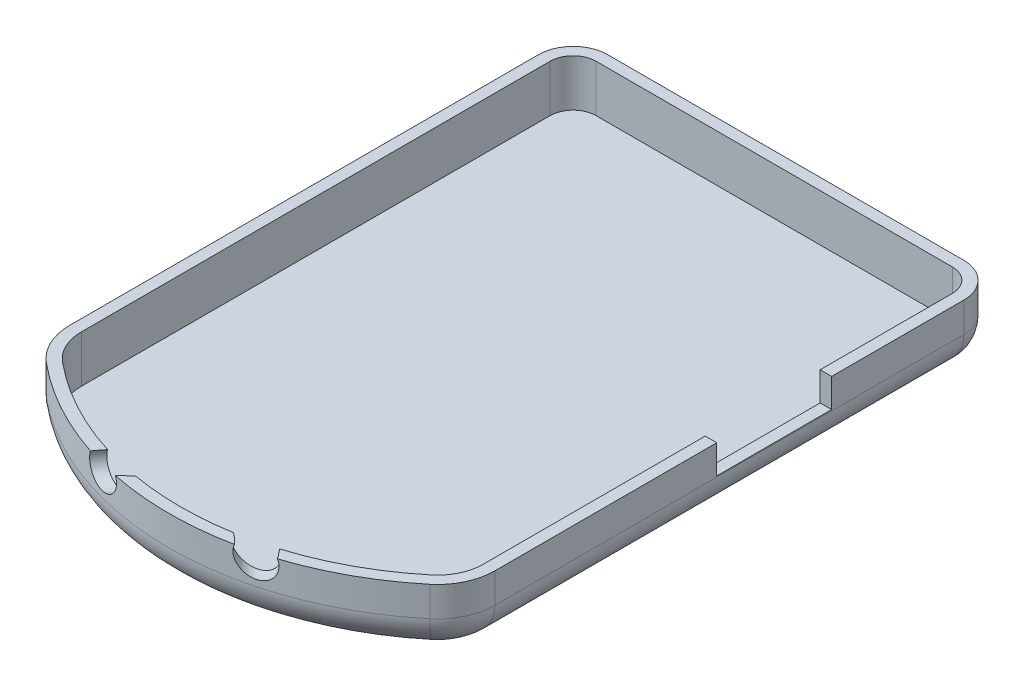
SolidWorks part; units mm, degrees
ref_plane "Front Plane" through (0, 0, 0) normal (0, 0, 1) x (1, 0, 0)
ref_plane "Top Plane" through (0, 0, 0) normal (0, 1, 0) x (1, 0, 0)
ref_plane "Right Plane" through (0, 0, 0) normal (1, 0, 0) x (0, 0, -1)
sketch "Sketch1" plane through (0, 0, 0) normal (0, 1, 0) x (1, 0, 0)
  line L0 (0, -43.7979) -> (0, -43)
  line L1 (3, 0) -> (34, 0)
  line L2 (0, -3) -> (0, -43)
  line L4 (37, -3) -> (37, -43)
  line L7 (37, -43) -> (37, -43.7979)
  arc A2 (34, 0) -> (37, -3) centre (34, -3) cw
  arc A3 (0, -3) -> (3, 0) centre (3, -3) cw
  arc A4 (35.1895, -47.6484) -> (1.8105, -47.6484) centre (18.5, -27.5) cw
  arc A5 (35.1895, -47.6484) -> (37, -43.7979) centre (32, -43.7979) ccw
  arc A6 (1.8105, -47.6484) -> (0, -43.7979) centre (5, -43.7979) cw
  point P9 (37, -46)
  point P12 (37, 0)
  point P15 (0, 0)
  dimension "D3" = 5
  dimension "D1" = 37
  dimension "D2" = 46
  dimension "D4" = 40
extrude "Boss-Extrude1" add sketch "Sketch1" along normal blind 1.5
ref_plane "Plane1" through (0, 1.5, 0) normal (0, 1, 0) x (1, 0, 0)
sketch "Sketch2" plane through (0, 1.5, 0) normal (0, 1, 0) x (1, 0, 0)
  line L0 (0, -43.7979) -> (0, -43)
  line L1 (3, 0) -> (34, 0)
  line L2 (0, -3) -> (0, -43)
  line L4 (37, -3) -> (37, -43)
  line L9 (37, -43) -> (37, -43.7979)
  line L10 (1, -43.7979) -> (1, -43)
  line L11 (1, -3) -> (1, -43)
  line L14 (3, -1) -> (34, -1)
  line L15 (36, -3) -> (36, -43)
  line L16 (36, -43) -> (36, -43.7979)
  arc A0 (34, 0) -> (37, -3) centre (34, -3) cw
  arc A3 (3, 0) -> (0, -3) centre (3, -3) ccw
  arc A8 (35.1895, -47.6484) -> (1.8105, -47.6484) centre (18.5, -27.5) cw
  arc A9 (1.8105, -47.6484) -> (0, -43.7979) centre (5, -43.7979) cw
  arc A10 (35.1895, -47.6484) -> (37, -43.7979) centre (32, -43.7979) ccw
  arc A14 (2.4484, -46.8783) -> (1, -43.7979) centre (5, -43.7979) cw
  arc A17 (3, -1) -> (1, -3) centre (3, -3) ccw
  arc A18 (34, -1) -> (36, -3) centre (34, -3) cw
  arc A19 (34.5516, -46.8783) -> (36, -43.7979) centre (32, -43.7979) ccw
  arc A20 (34.5516, -46.8783) -> (2.4484, -46.8783) centre (18.5, -27.5) cw
  point P7 (37, 0)
  point P12 (37, -46)
  point P15 (0, 0)
  point P22 (36, -1)
  point P25 (36, -45)
  point P30 (1, -1)
  point P38 (37, -46)
  point P40 (35.5, -43.7979)
  point P41 (32, -43.7979)
  point P42 (34.2327, -46.4933)
  point P44 (2.7673, -46.4933)
  point P45 (5, -43.7979)
  point P46 (1.5, -43.7979)
  dimension "D3" = 3
  dimension "D9" = 5
  dimension "D1" = 37
  dimension "D2" = 46
  dimension "D4" = 35
  dimension "D5" = 44
  dimension "D7" = 1
extrude "Boss-Extrude2" add sketch "Sketch2" along normal blind 1.6
ref_plane "Plane2" through (0, 3.1, 0) normal (0, 1, 0) x (1, 0, 0)
sketch "Sketch3" plane through (0, 3.1, 0) normal (0, 1, 0) x (1, 0, 0)
  line L0 (0, -43.7979) -> (0, -43)
  line L1 (3, 0) -> (34, 0)
  line L2 (0, -3) -> (0, -43)
  line L4 (37, -3) -> (37, -14.5)
  line L9 (37, -43) -> (37, -43.7979)
  line L15 (36, -14.5) -> (37, -14.5)
  line L16 (36, -24.5) -> (37, -24.5)
  line L17 (37, -24.5) -> (37, -43)
  line L19 (36, -25.5) -> (36, -43)
  line L20 (36, -43) -> (36, -43.7979)
  line L21 (1, -43.7979) -> (1, -43)
  line L22 (1, -3) -> (1, -43)
  line L23 (3, -1) -> (34, -1)
  line L24 (36, -3) -> (36, -13.5)
  line L25 (36, -25.5) -> (36, -24.5)
  line L26 (36, -13.5) -> (36, -14.5)
  line L28 (35.5, -14.5) -> (37, -14.5) construction
  line L29 (35.5, -13.5) -> (36, -13.5) construction
  line L32 (35.5, -24.5) -> (37, -24.5) construction
  line L33 (35.5, -25.5) -> (36, -25.5) construction
  arc A0 (34, 0) -> (37, -3) centre (34, -3) cw
  arc A3 (3, 0) -> (0, -3) centre (3, -3) ccw
  arc A8 (35.1895, -47.6484) -> (1.8105, -47.6484) centre (18.5, -27.5) cw
  arc A9 (1.8105, -47.6484) -> (0, -43.7979) centre (5, -43.7979) cw
  arc A10 (35.1895, -47.6484) -> (37, -43.7979) centre (32, -43.7979) ccw
  arc A11 (34.5516, -46.8783) -> (36, -43.7979) centre (32, -43.7979) ccw
  arc A12 (34.5516, -46.8783) -> (2.4484, -46.8783) centre (18.5, -27.5) cw
  arc A13 (2.4484, -46.8783) -> (1, -43.7979) centre (5, -43.7979) cw
  arc A14 (3, -1) -> (1, -3) centre (3, -3) ccw
  arc A15 (34, -1) -> (36, -3) centre (34, -3) cw
  point P32 (35.5, -3)
  point P33 (35.5, -43)
  dimension "D1" = 3
  dimension "D5" = 5
  dimension "D2" = 14.5
  dimension "D3" = 1
  dimension "D6" = 10
extrude "Boss-Extrude3" add sketch "Sketch3" along normal blind 2.5
fillet "Fillet1" radius 3 8 edges at (18.5, 0, 0) (36.1213, 0, 0.8787) (0.8787, 0, 0.8787) (37, 0, 23.3989) (36.5248, 0, 45.9253) (18.5, 0, 53.663) (0.4752, 0, 45.9253) (0, 0, 23.3989)
ref_plane "Plane3" through (0, 5.05, 0) normal (0, 1, 0) x (1, 0, 0)
sketch "Sketch4" plane through (0, 5.05, 0) normal (0, 1, 0) x (1, 0, 0)
  arc A0 (26.4544, -55.0038) -> (10.548, -54.9973) centre (18.5, -58) ccw
  dimension "D2" = 58
  dimension "D3" = 8.5
  dimension "D1" = 18.5
sweep "Cut-Sweep1" cut path "Sketch4" circular profile diameter 3 parameters "D3"=3
sketch "Sketch7" plane through (0, 1.5, 0) normal (0, 1, 0) x (1, 0, 0)
  point P0 (10, -48.5)
  point P2 (27, -48.5)
  dimension "D1" = 17
  dimension "D2" = 10
  dimension "D3" = 48.5
hole_wizard "Ø3.8 (3.8) Diameter Hole1" [suppressed] positions "Sketch7" profile "Sketch6" hole size "Ø3.8" standard "ISO"
sketch "Sketch6" plane through (10, 1.5, 48.5) normal (1, 0, 0) x (0, 0, 1)
  line L0 (0, 0) -> (0, 1.5)
  line L1 (0, 1.5) -> (1.9, 1.5)
  line L2 (1.9, 1.5) -> (1.9, 0)
  line L5 (1.9, 0) -> (0, 0)
  line L11 (0, -6.35) -> (0, 107.95) construction
  dimension "Thru Hole Dia." = 3.8
  dimension "Thru Hole Depth" = 1.5
sketch "Sketch8" plane through (0, 1.5, 0) normal (0, 1, 0) x (1, 0, 0)
  line L0 (3, -1) -> (34, -1)
  line L1 (1, -3) -> (1, -43.7979)
  line L3 (36, -43.7979) -> (36, -3)
  line L4 (3, -44.5) -> (34, -44.5)
  line L5 (1, -43.7979) -> (1.0621, -44.5)
  line L6 (1.0621, -44.5) -> (3, -44.5)
  line L7 (36, -43.7979) -> (35.9379, -44.5)
  line L8 (35.9379, -44.5) -> (34, -44.5)
  arc A0 (1, -3) -> (3, -1) centre (3, -3) cw
  arc A1 (34, -1) -> (36, -3) centre (34, -3) cw
  arc A2 (36, -3) -> (34, -1) centre (34, -3) ccw construction
  arc A3 (1, -43.7979) -> (2.4484, -46.8783) centre (5, -43.7979) ccw construction
  arc A4 (34.5516, -46.8783) -> (36, -43.7979) centre (32, -43.7979) ccw construction
  dimension "D1" = 43.5
extrude "Cut-Extrude1" [suppressed] cut sketch "Sketch8" against normal blind 0.5
